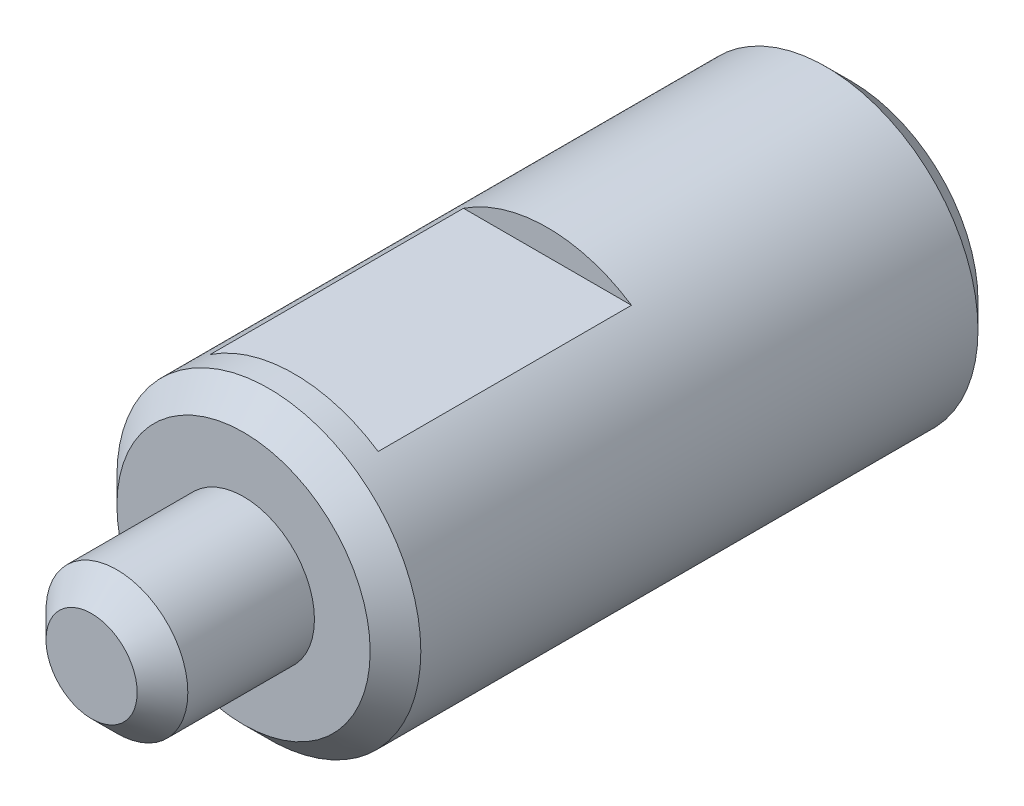
SolidWorks part; units mm, degrees
ref_plane "前视基准面" through (0, 0, 0) normal (0, 0, 1) x (1, 0, 0)
ref_plane "上视基准面" through (0, 0, 0) normal (0, 1, 0) x (1, 0, 0)
ref_plane "右视基准面" through (0, 0, 0) normal (1, 0, 0) x (0, 0, -1)
sketch "草图1" plane through (0, 0, 0) normal (0, 0, 1) x (1, 0, 0)
  circle A0 centre (0, 0) radius 3
  dimension "D1" = 6
extrude "凸台-拉伸1" add sketch "草图1" along normal blind 12
sketch "草图2" plane through (0, 0, 12) normal (0, 0, 1) x (1, 0, 0)
  circle A0 centre (0, 0) radius 1.4
  dimension "D1" = 2.8
extrude "凸台-拉伸2" add sketch "草图2" along normal blind 3
chamfer "倒角1" distance 0.5 angle 45 3 edges at (3, 0, 12) (1.4, 0, 15) (3, 0, 0)
hole_wizard "M3 螺纹孔1" positions "草图6" profile "草图5" tap size "M3" standard "GB"
sketch "草图6" plane through (0, 0, 0) normal (0, 0, -1) x (-1, 0, 0)
  point P1 (0, 0)
sketch "草图5" plane through (0, 0, 0) normal (1, 0, 0) x (0, 1, 0)
  line L0 (0, 0) -> (0, 8.2511)
  line L1 (0, 8.2511) -> (1.25, 7.5)
  line L2 (1.25, 7.5) -> (1.25, 0)
  line L5 (1.25, 0) -> (0, 0)
  line L10 (0, 8.2511) -> (-1.25, 7.5) construction
  line L11 (0, -6.35) -> (0, 107.95) construction
  dimension "螺纹孔钻头直径" = 2.5
  dimension "螺纹孔钻头深度" = 7.5
  dimension "导头角度" = 118
ref_plane "基准面1" through (0, 3, 0) normal (0, 1, 0) x (-1, 0, 0)
sketch "草图7" plane through (0, 3, 0) normal (0, 1, 0) x (-1, 0, 0)
  line L0 (2.5, 12) -> (-2.5, 12) construction
  line L1 (-4.8512, 11) -> (4.8512, 11)
  line L2 (-4.8512, 11) -> (-4.8512, 6)
  line L3 (-4.8512, 6) -> (4.8512, 6)
  line L4 (4.8512, 11) -> (4.8512, 6)
  line L5 (-4.8512, 11) -> (4.8512, 6) construction
  line L6 (-4.8512, 6) -> (4.8512, 11) construction
  point P0 (0, 8.5)
  dimension "D1" = 5
  dimension "D2" = 3.5
extrude "切除-拉伸1" cut sketch "草图7" against normal blind 0.5
mirror "镜向1" about plane through (0, 0, 0) normal (0, 1, 0) of "切除-拉伸1"
